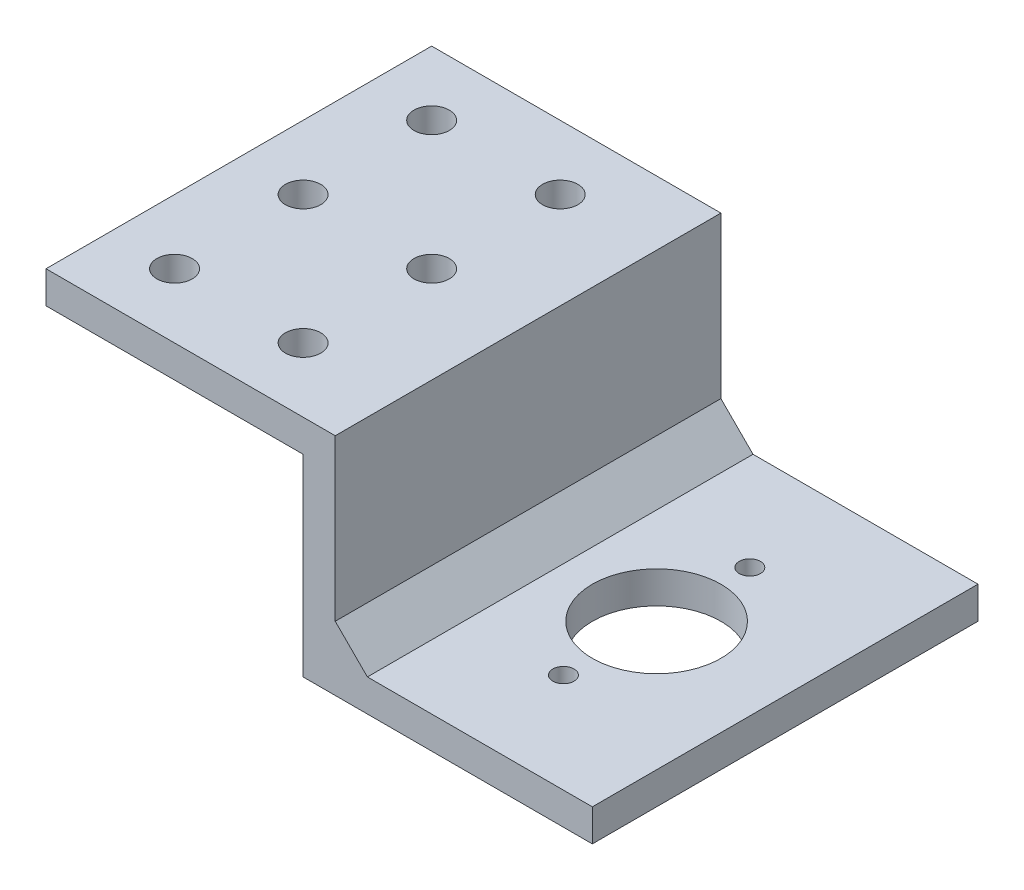
SolidWorks part; units mm, degrees
ref_plane "前视基准面" through (0, 0, 0) normal (0, 0, 1) x (1, 0, 0)
ref_plane "上视基准面" through (0, 0, 0) normal (0, 1, 0) x (1, 0, 0)
ref_plane "右视基准面" through (0, 0, 0) normal (1, 0, 0) x (0, 0, -1)
sketch "草图1" plane through (0, 0, 0) normal (0, 0, 1) x (1, 0, 0)
  line L0 (0, 0) -> (-45, 0)
  line L1 (-45, 0) -> (-45, 30)
  line L2 (-45, 30) -> (-85, 30)
  line L3 (-85, 30) -> (-85, 35)
  line L4 (-85, 35) -> (-40, 35)
  line L5 (-40, 35) -> (-40, 5)
  line L6 (-40, 5) -> (0, 5)
  line L7 (0, 5) -> (0, 0)
  point P8 (-20, 5)
  dimension "D1" = 5
  dimension "D2" = 5
  dimension "D3" = 5
  dimension "D4" = 40
  dimension "D5" = 30
  dimension "D6" = 25
extrude "凸台-拉伸1" add sketch "草图1" along normal blind 60
sketch "草图2" plane through (0, 30, 0) normal (0, -1, 0) x (1, 0, 0)
  line L0 (-55, 60) -> (-55, 0) construction
  line L1 (-85, 60) -> (-45, 60) construction
  line L2 (-85, 0) -> (-45, 0) construction
  line L3 (-75, 60) -> (-75, 0) construction
  line L4 (-85, 30) -> (-45, 30) construction
  line L5 (-85, 60) -> (-85, 0) construction
  line L6 (-45, 60) -> (-45, 0) construction
  line L7 (-45, 60) -> (-45, 0) construction
  circle A0 centre (-55, 50) radius 2.75
  circle A1 centre (-55, 30) radius 2.75
  circle A3 centre (-75, 30) radius 2.75
  circle A4 centre (-55, 10) radius 2.75
  circle A6 centre (-75, 50) radius 2.75
  circle A7 centre (-75, 10) radius 2.75
  dimension "D1" = 30
  dimension "D2" = 10
  dimension "D4" = 20
  dimension "D3" = 5.5
extrude "切除-拉伸1" cut sketch "草图2" against normal through all
sketch "草图3" plane through (0, 5, 0) normal (0, 1, 0) x (1, 0, 0)
  line L0 (-20, 0) -> (-20, -60) construction
  line L1 (0, 0) -> (-40, 0) construction
  line L2 (0, -60) -> (-40, -60) construction
  line L3 (-20, -30) -> (0, -30) construction
  line L4 (0, -60) -> (0, 0) construction
  circle A0 centre (-20, -30) radius 10
  circle A1 centre (-20, -15.5) radius 1.65
  circle A2 centre (-20, -44.5) radius 1.65
  dimension "D1" = 20
  dimension "D2" = 3.3
  dimension "D3" = 29
extrude "切除-拉伸2" cut sketch "草图3" against normal through all
chamfer "倒角1" distance 5 angle 45 1 edges at (-40, 5, 30)
